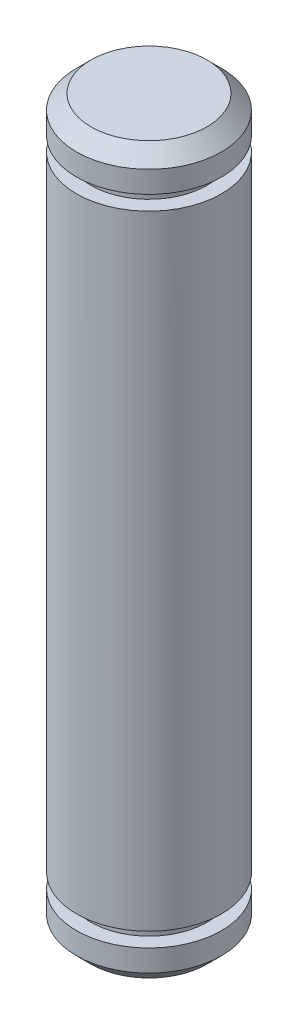
SolidWorks part; units mm, degrees
ref_plane "Front Plane" through (0, 0, 0) normal (0, 0, 1) x (1, 0, 0)
ref_plane "Top Plane" through (0, 0, 0) normal (0, 1, 0) x (1, 0, 0)
ref_plane "Right Plane" through (0, 0, 0) normal (1, 0, 0) x (0, 0, -1)
sketch "Sketch1" plane through (0, 0, 0) normal (0, 1, 0) x (1, 0, 0)
  circle A0 centre (0, 0) radius 5
  dimension "D1" = 10
extrude "Boss-Extrude1" add sketch "Sketch1" along normal blind 50
chamfer "Chamfer1" distance 1 angle 45 2 edges at (0, 50, 5) (0, 0, 5)
sketch "Sketch2" plane through (0, 0, 0) normal (0, -1, 0) x (1, 0, 0)
  circle A0 centre (0, 0) radius 4
  circle A1 centre (0, 0) radius 6
  dimension "D1" = 12
  dimension "D2" = 8
extrude "Cut-Extrude1" cut sketch "Sketch2" against normal blind 1 from offset 2.5 offset against normal yes
sketch "Sketch3" plane through (0, 50, 0) normal (0, 1, 0) x (1, 0, 0)
  circle A0 centre (0, 0) radius 4
  circle A1 centre (0, 0) radius 5
  dimension "D1" = 10
  dimension "D2" = 8
extrude "Cut-Extrude2" cut sketch "Sketch3" against normal blind 1 from offset 2.5 offset against normal yes
